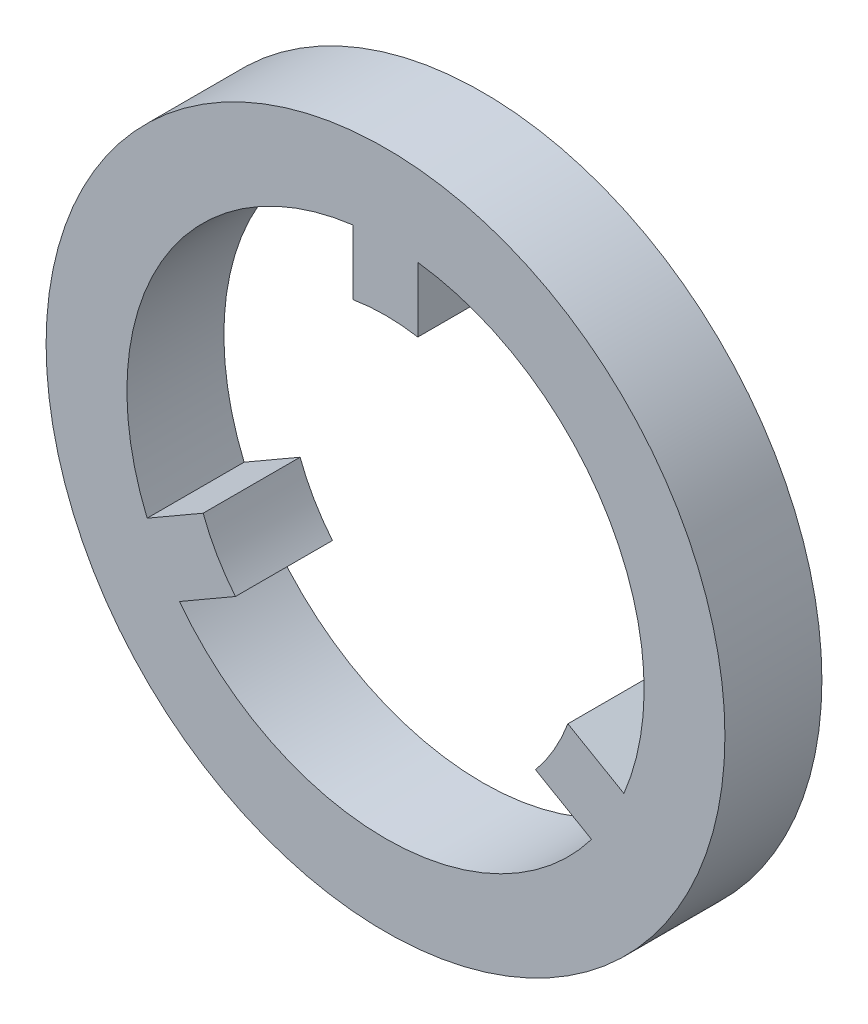
SolidWorks part; units mm, degrees
ref_plane "Front Plane" through (0, 0, 0) normal (0, 0, 1) x (1, 0, 0)
ref_plane "Top Plane" through (0, 0, 0) normal (0, 1, 0) x (1, 0, 0)
ref_plane "Right Plane" through (0, 0, 0) normal (1, 0, 0) x (0, 0, -1)
sketch "Sketch1" plane through (0, 0, 0) normal (0, 0, 1) x (1, 0, 0)
  line L0 (0, 0) -> (0, 8) construction
  line L1 (-1, 7.9373) -> (1, 7.9373) construction
  line L2 (-1, 7.9373) -> (-1, 5.9373)
  line L4 (1, 7.9373) -> (1, 5.9373)
  line L5 (7.3739, -3.1026) -> (5.6418, -2.1026)
  line L6 (6.3739, -4.8347) -> (4.6418, -3.8347)
  line L7 (-6.3739, -4.8347) -> (-4.6418, -3.8347)
  line L8 (-7.3739, -3.1026) -> (-5.6418, -2.1026)
  circle A0 centre (0, 0) radius 8
  circle A1 centre (0, 0) radius 10.5
  circle A2 centre (0, 0) radius 6.0209
  point P8 (0, 7.9373)
  point P12 (0, 0)
  point P13 (0, 0)
  point P21 (0, 0)
  dimension "D1" = 16
  dimension "D2" = 21
  dimension "D3" = 2
  dimension "D4" = 2
  dimension "D5" = 3
extrude "Boss-Extrude1" add sketch "Sketch1" along normal blind 3 contours A1 A0 | A2 L4 A0 L2 | A2 L6 A0 L5 | A2 L8 A0 L7
